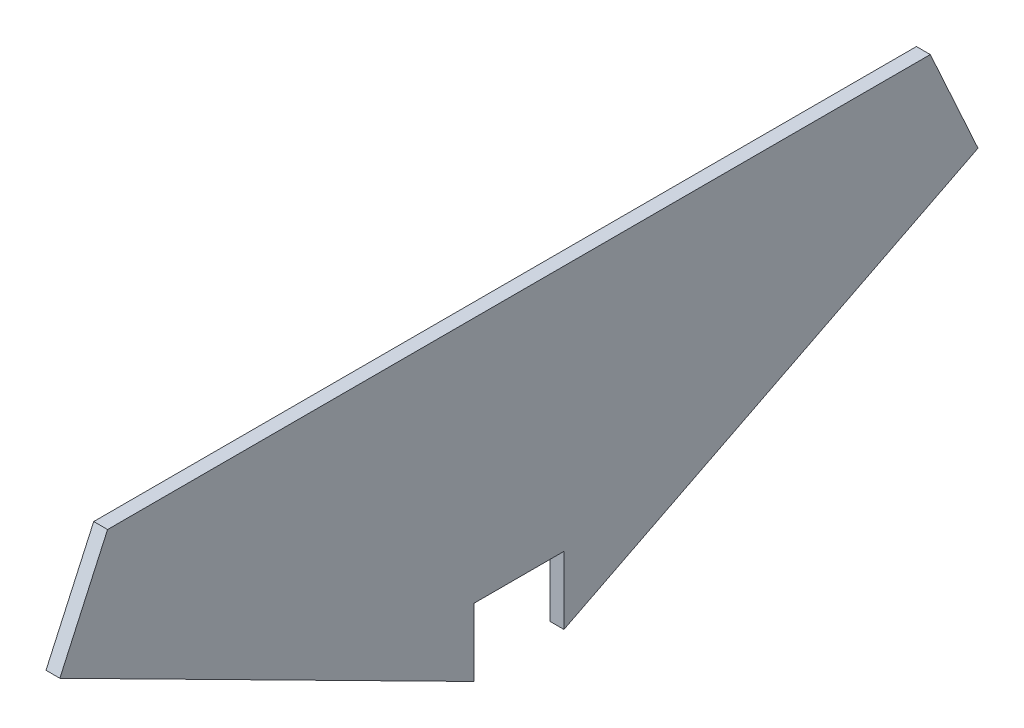
SolidWorks part; units mm, degrees
material "ASTM A36 Steel"
ref_plane "Front Plane" through (0, 0, 0) normal (0, 0, 1) x (1, 0, 0)
ref_plane "Top Plane" through (0, 0, 0) normal (0, 1, 0) x (1, 0, 0)
ref_plane "Right Plane" through (0, 0, 0) normal (1, 0, 0) x (0, 0, -1)
sketch "Sketch1" plane through (0, 0, 0) normal (1, 0, 0) x (0, 0, -1)
  line L8 (173.4298, 75.1105) -> (-182.8581, 75.1105)
  line L9 (-182.8581, 75.1105) -> (-203.5212, 29.6516)
  line L10 (-203.5212, 29.6516) -> (-24.2142, -61.1936)
  line L11 (-24.2142, -61.1936) -> (-24.2142, -31.8895)
  line L12 (-24.2142, -31.8895) -> (14.7858, -31.8895)
  line L13 (14.7858, -61.1936) -> (14.7858, -31.8895)
  line L14 (194.0929, 29.6516) -> (14.7858, -61.1936)
  line L15 (173.4298, 75.1105) -> (194.0929, 29.6516)
extrude "Boss-Extrude1" add sketch "Sketch1" along normal blind 6
